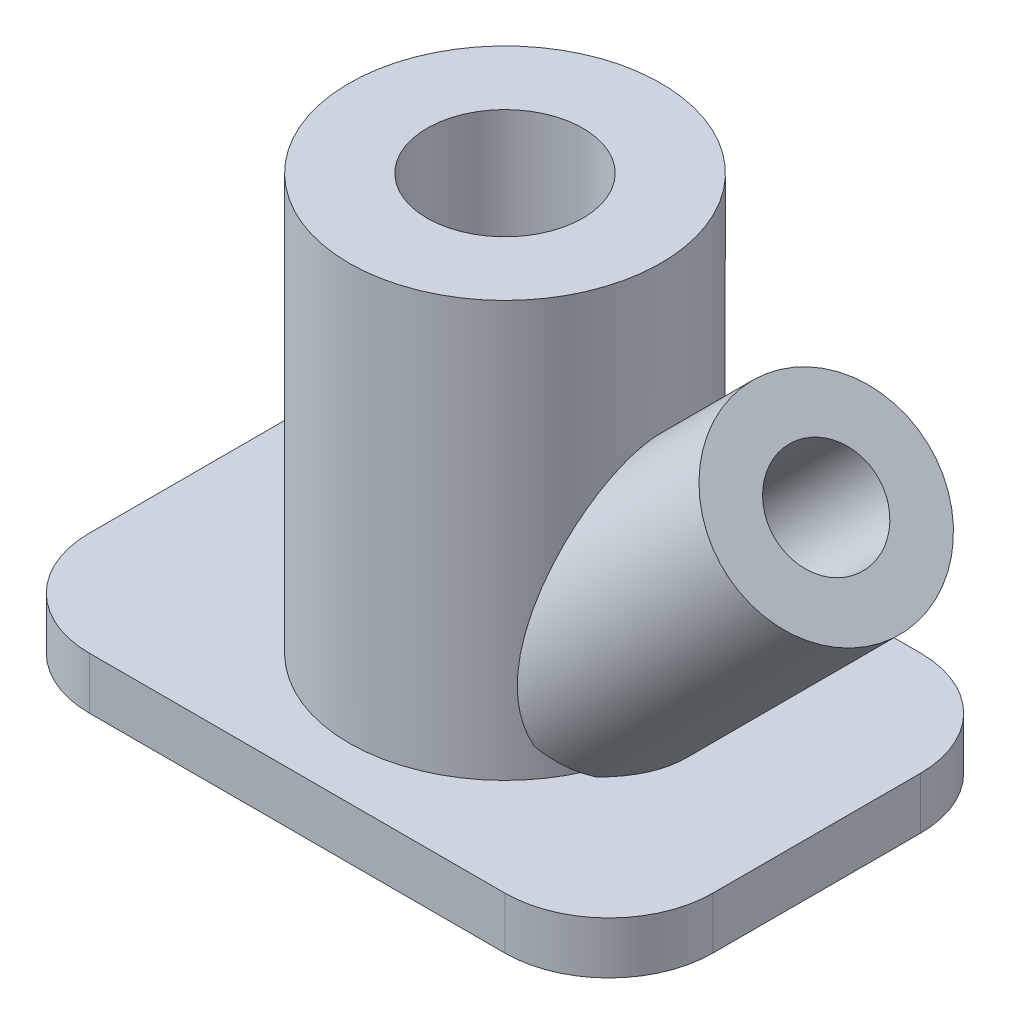
SolidWorks part; units mm, degrees
ref_plane "Alzado" through (0, 0, 0) normal (0, 0, 1) x (1, 0, 0)
ref_plane "Planta" through (0, 0, 0) normal (0, 1, 0) x (1, 0, 0)
ref_plane "Vista lateral" through (0, 0, 0) normal (1, 0, 0) x (0, 0, -1)
sketch "Croquis1" plane through (0, 0, 0) normal (0, 1, 0) x (1, 0, 0)
  line L1 (-60, -40) -> (60, -40)
  line L2 (-60, -40) -> (-60, 40)
  line L3 (-60, 40) -> (60, 40)
  line L4 (60, -40) -> (60, 40)
  line L5 (-60, -40) -> (60, 40) construction
  line L6 (-60, 40) -> (60, -40) construction
  point P0 (0, 0)
extrude "Saliente-Extruir1" add sketch "Croquis1" along normal blind 10
fillet "Redondeo1" radius 20 4 edges at (-60, 5, -40) (-60, 5, 40) (60, 5, 40) (60, 5, -40)
sketch "Croquis2" plane through (0, 0, 0) normal (0, 1, 0) x (1, 0, 0)
  circle A0 centre (0, 0) radius 30
extrude "Saliente-Extruir2" add sketch "Croquis2" along normal blind 90
sketch "Croquis3" plane through (0, 90, 0) normal (0, 1, 0) x (1, 0, 0)
  circle A0 centre (0, 0) radius 15
extrude "Cortar-Extruir1" cut sketch "Croquis3" against normal up to vertex (90 mm away) up to point (0, 0, 0)
sketch "Croquis4" plane through (0, 0, 0) normal (0, 0, 1) x (1, 0, 0)
  line L0 (30, 33.3803) -> (61.8198, 65.2001) construction
  line L1 (30, 10) -> (30, 90) construction
  line L2 (54.3143, 72.7057) -> (61.8198, 65.2001) construction
  line L3 (61.8198, 65.2001) -> (72.0443, 54.9756) construction
  point P5 (0, 0)
  point P7 (0, 0)
  dimension "D1" = 135
  dimension "D2" = 90
ref_plane "Plano1" through (63.51, 63.51, 0) normal (0.7071, 0.7071, 0) x (0, 0, -1)
sketch "Croquis6" plane through (63.51, 63.51, 0) normal (0.7071, 0.7071, 0) x (0, 0, -1)
  circle A0 centre (0, 2.3902) radius 20
extrude "Saliente-Extruir3" add sketch "Croquis6" against normal blind 62
sketch "Croquis7" plane through (63.51, 63.51, 0) normal (0.7071, 0.7071, 0) x (0, 0, -1)
  circle A0 centre (0, 2.3902) radius 10
extrude "Cortar-Extruir3" cut sketch "Croquis7" against normal blind 62
sketch "Croquis8" plane through (0, 0, 0) normal (0, 1, 0) x (1, 0, 0)
  circle A0 centre (0, 0) radius 15
extrude "Cortar-Extruir5" cut sketch "Croquis8" against normal blind 67 and the other way blind 90
sketch "Croquis9" plane through (63.51, 63.51, 0) normal (0.7071, 0.7071, 0) x (0, 0, -1)
  circle A0 centre (0, 2.3902) radius 10
extrude "Cortar-Extruir7" cut sketch "Croquis9" against normal blind 80
